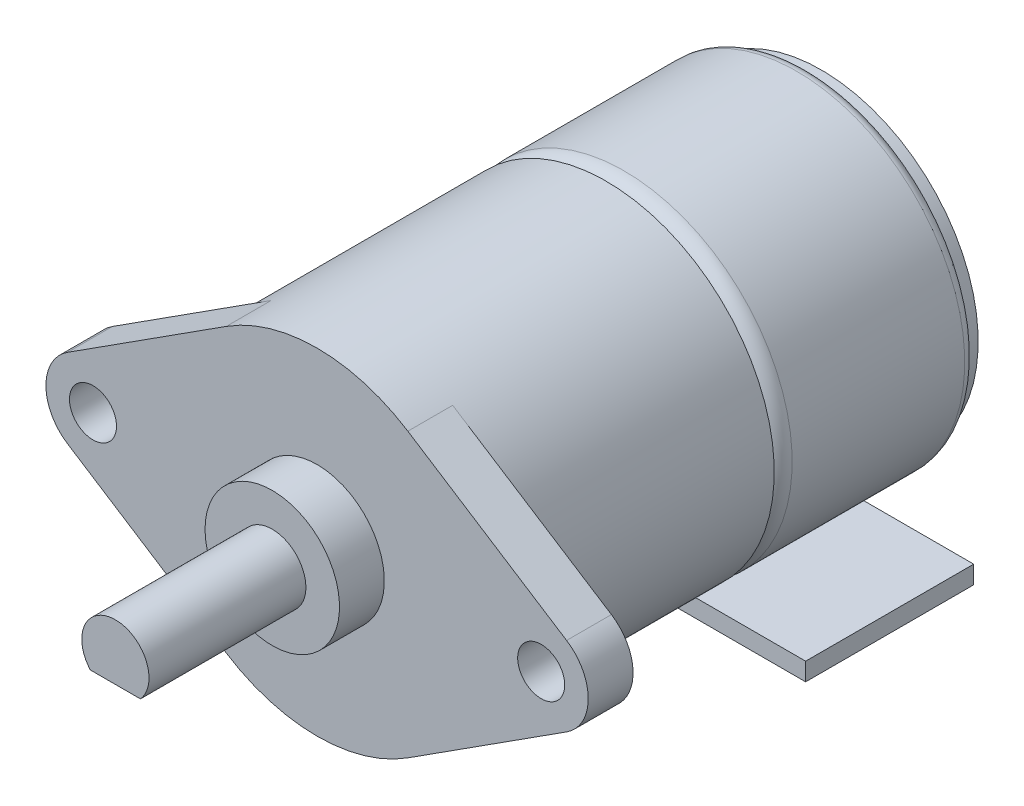
SolidWorks part; units mm, degrees
ref_plane "Front" through (0, 0, 0) normal (0, 0, 1) x (1, 0, 0)
ref_plane "Top" through (0, 0, 0) normal (0, 1, 0) x (1, 0, 0)
ref_plane "Right" through (0, 0, 0) normal (1, 0, 0) x (0, 0, -1)
sketch "Эскиз1" plane through (0, 0, 0) normal (0, 1, 0) x (1, 0, 0)
  line L0 (0, 0) -> (0, -39.2335) construction
  line L1 (0, 0) -> (-0.75, 0)
  line L2 (-0.75, 0) -> (-0.75, -0.5)
  line L3 (-0.75, -0.5) -> (-3, -0.5)
  line L4 (-3, -0.5) -> (-3, -1.5)
  line L5 (-3, -1.5) -> (-7, -1.5)
  line L6 (-7, -1.5) -> (-7, -2.1)
  line L8 (-7.5, -2.6) -> (-7.5, -10.3)
  line L10 (-6.7, -11.1) -> (-6.7, -12) construction
  line L11 (-6.7, -12) -> (0, -12) construction
  line L12 (0, -12) -> (0, 0)
  line L14 (-7, -2.1) -> (-7, -2.6) construction
  line L15 (-6.7, -11.1) -> (-6.7, -10.3) construction
  line L16 (-6.7, -11.1) -> (-7.5, -11.1)
  line L17 (-7.5, -11.1) -> (-7.5, -24)
  line L18 (-7.5, -24) -> (-3, -24)
  line L19 (-3, -24) -> (-3, -26)
  line L20 (-3, -26) -> (-1.5, -26)
  line L21 (-1.5, -26) -> (-1.5, -33)
  line L22 (-1.5, -33) -> (0, -33)
  line L23 (0, -33) -> (0, -12)
  arc A0 (-7, -2.1) -> (-7.5, -2.6) centre (-7, -2.6) ccw
  arc A1 (-7.5, -10.3) -> (-6.7, -11.1) centre (-6.7, -10.3) ccw
  dimension "D1" = 6
  dimension "D7" = 0.9
  dimension "D10" = 10.5
  dimension "D2" = 15
  dimension "D3" = 1
  dimension "D4" = 1.5
  dimension "D5" = 0.5
  dimension "D6" = 0.6
  dimension "D8" = 14
  dimension "D9" = 6.7
  dimension "D11" = 22.5
  dimension "D12" = 6
  dimension "D13" = 2
  dimension "D14" = 7
  dimension "D15" = 3
revolve "Motor" add sketch "Эскиз1" angle 360 about L0
sketch "Эскиз2" plane through (0, 0, 33) normal (0, 0, 1) x (1, 0, 0)
  line L0 (-1.118, -1) -> (1.118, -1)
  line L1 (-1.6853, 1.5) -> (1.9295, 1.5) construction
  arc A0 (1.118, -1) -> (-1.118, -1) centre (0, 0) ccw
  circle A1 centre (0, 0) radius 1.5 construction
  dimension "D1" = 2.5
extrude "Шпон-паз" cut sketch "Эскиз2" against normal blind 6.5 thin
sketch "Эскиз3" plane through (0, 0, 24) normal (0, 0, 1) x (1, 0, 0)
  line L0 (4.05, 6.3125) -> (11.134, 1.7675)
  line L1 (11.134, -1.7675) -> (4.05, -6.3125)
  line L2 (-10, 0) -> (10, 0) construction
  line L3 (-4.05, -6.3125) -> (-11.134, -1.7675)
  line L4 (-4.05, 6.3125) -> (-11.134, 1.7675)
  circle A0 centre (0, 0) radius 7.5 construction
  arc A1 (11.134, 1.7675) -> (11.134, -1.7675) centre (10, 0) cw
  circle A2 centre (10, 0) radius 1.05
  arc A3 (4.05, -6.3125) -> (-4.05, -6.3125) centre (0, 0) cw
  circle A4 centre (-10, 0) radius 1.05
  arc A5 (-11.134, -1.7675) -> (-11.134, 1.7675) centre (-10, 0) cw
  arc A6 (4.05, 6.3125) -> (-4.05, 6.3125) centre (0, 0) ccw
  point P12 (0, 0)
  dimension "D1" = 2.1
  dimension "D2" = 2.1
  dimension "D3" = 20
extrude "Держатель" add sketch "Эскиз3" against normal blind 2
ref_plane "Плоскость1" through (0, -7.5, 0) normal (0, -1, 0) x (-1, 0, 0)
sketch "Эскиз4" plane through (0, -7.5, 0) normal (0, -1, 0) x (-1, 0, 0)
  line L0 (0, -2.6) -> (0, -10.3) construction
  line L1 (3.5, -10.2) -> (-8, -10.2)
  line L2 (3.5, -10.2) -> (3.5, -2.7)
  line L3 (3.5, -2.7) -> (-8, -2.7)
  line L4 (-8, -10.2) -> (-8, -2.7)
  line L5 (3.5, -6.45) -> (-8, -6.45) construction
  line L7 (7.5, -10.3) -> (-7.5, -10.3) construction
  line L8 (7.5, -2.6) -> (-7.5, -2.6) construction
  point P5 (0, -6.45)
  dimension "D1" = 7.5
  dimension "D2" = 11.5
  dimension "D3" = 3.5
extrude "Плата" add sketch "Эскиз4" along normal blind 0.8 separate body
sketch "Пайка контактов" plane through (0, -8.3, 0) normal (0, -1, 0) x (1, 0, 0)
  line L0 (-0.75, 7.2) -> (2.25, 7.2) construction
  line L1 (0.75, 5.7) -> (-2.25, 5.7) construction
  line L2 (-0.75, 5.7) -> (-0.75, 7.2) construction
  line L3 (-0.75, 6.45) -> (-3.5, 6.45) construction
  line L4 (-3.5, 10.2) -> (-3.5, 2.7) construction
  line L5 (-0.75, 7.2) -> (0.75, 5.7) construction
  line L6 (0, 6.45) -> (0, 0) construction
  line L8 (7, 5.5333) -> (7, 3.7) construction
  line L9 (7, 7.3667) -> (7, 5.5333) construction
  line L10 (7, 7.3667) -> (7, 9.2) construction
  line L11 (7, 6.45) -> (8, 6.45) construction
  line L12 (8, 2.7) -> (8, 10.2) construction
  circle A0 centre (-2.25, 5.7) radius 0.75
  circle A1 centre (-0.75, 7.2) radius 0.75
  circle A2 centre (0.75, 5.7) radius 0.75
  circle A3 centre (2.25, 7.2) radius 0.75
  circle A4 centre (7, 3.7) radius 0.75
  circle A5 centre (7, 5.5333) radius 0.75
  circle A6 centre (7, 7.3667) radius 0.75
  circle A7 centre (7, 9.2) radius 0.75
  point P14 (-3.5, 6.45)
  point P29 (8, 6.45)
  dimension "D1" = 1.5
  dimension "D4" = 1.5
  dimension "D2" = 3
  dimension "D3" = 1.5
  dimension "D5" = 5.5
  dimension "D6" = 1
extrude "Бобышка-Вытянуть3" add sketch "Пайка контактов" along normal blind 0.7 draft 35
sketch "Эскиз6" plane through (0, -8.3, 0) normal (0, -1, 0) x (1, 0, 0)
  line L0 (5.7717, 10.2) -> (5.7717, 2.7) construction
  line L1 (8, 10.2) -> (-3.5, 10.2) construction
  line L2 (-3.5, 2.7) -> (8, 2.7) construction
  line L3 (-3.5, 8.1932) -> (8, 8.1932) construction
  line L4 (-3.5, 10.2) -> (-3.5, 2.7) construction
  line L5 (8, 2.7) -> (8, 10.2) construction
  text T0 "B1 B2 A1 A2" font "Century Gothic" height 0.85
  text T1 " B1 A2 B2 A1" font "Century Gothic" height 0.8
extrude "Бобышка-Вытянуть4" add sketch "Эскиз6" along normal blind 0.01
